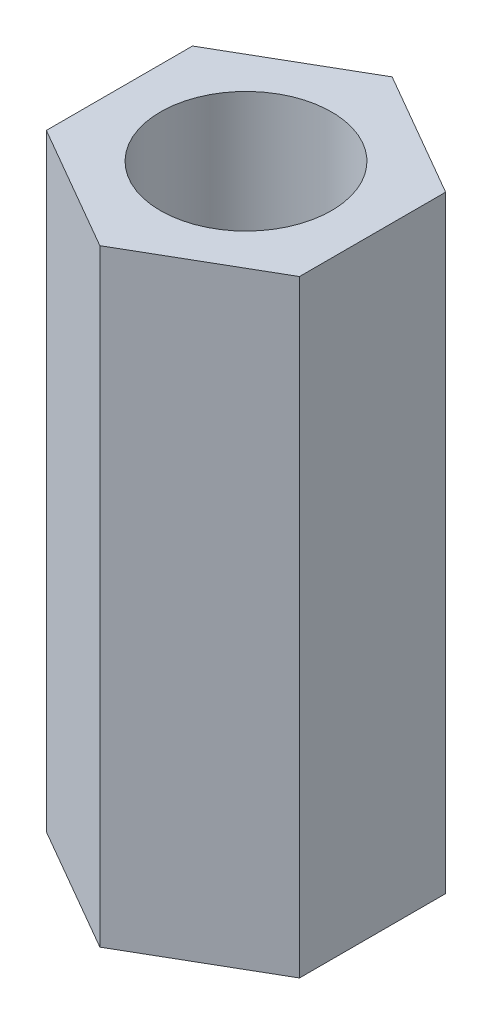
SolidWorks part; units mm, degrees
ref_plane "Front Plane" through (0, 0, 0) normal (0, 0, 1) x (1, 0, 0)
ref_plane "Top Plane" through (0, 0, 0) normal (0, 1, 0) x (1, 0, 0)
ref_plane "Right Plane" through (0, 0, 0) normal (1, 0, 0) x (0, 0, -1)
sketch "Sketch2" plane through (0, 0, 0) normal (0, 1, 0) x (1, 0, 0)
  line L0 (0, 2.887) -> (2.5002, 1.4435)
  line L1 (2.5002, 1.4435) -> (2.5002, -1.4435)
  line L2 (2.5002, -1.4435) -> (0, -2.887)
  line L3 (0, -2.887) -> (-2.5002, -1.4435)
  line L4 (-2.5002, -1.4435) -> (-2.5002, 1.4435)
  line L5 (-2.5002, 1.4435) -> (0, 2.887)
  circle A0 centre (0, 0) radius 1.69
  dimension "D2" = 3.38
  dimension "D3" = 2.887
extrude "Boss-Extrude1" add sketch "Sketch2" along normal blind 12
